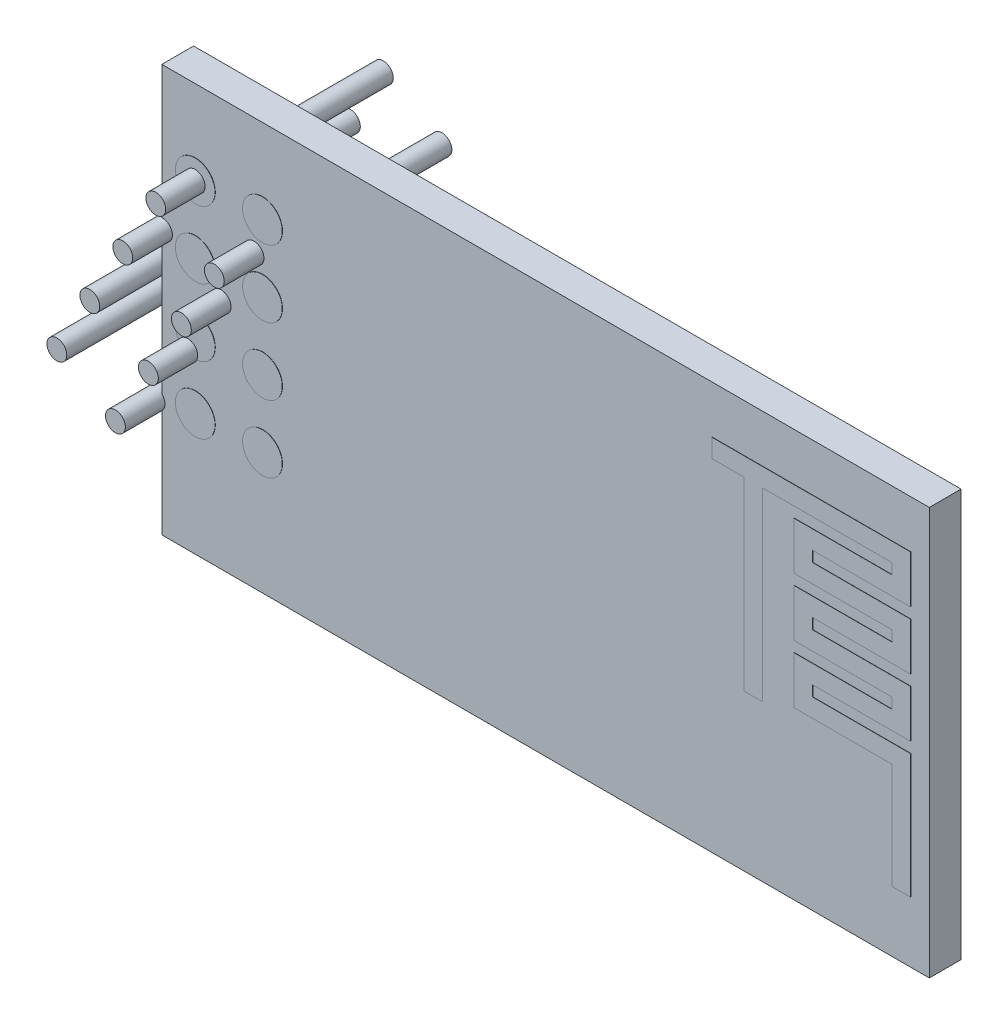
SolidWorks part; units mm, degrees
ref_plane "Front Plane" through (0, 0, 0) normal (0, 0, 1) x (1, 0, 0)
ref_plane "Top Plane" through (0, 0, 0) normal (0, 1, 0) x (1, 0, 0)
ref_plane "Right Plane" through (0, 0, 0) normal (1, 0, 0) x (0, 0, -1)
sketch "Sketch2" plane through (0, 0, 0) normal (0, 0, 1) x (1, 0, 0)
  line L1 (0, 0) -> (29, 0)
  line L2 (0, 0) -> (0, 15.4)
  line L3 (0, 15.4) -> (29, 15.4)
  line L4 (29, 0) -> (29, 15.4)
  dimension "D1" = 29
  dimension "D2" = 15.4
extrude "Boss-Extrude1" add sketch "Sketch2" along normal blind 1.2
sketch "Sketch3" plane through (0, 0, 1.2) normal (0, 0, 1) x (1, 0, 0)
  line L0 (0, 15.4) -> (0, 0) construction
  line L1 (29, 15.4) -> (0, 15.4) construction
  circle A0 centre (1.27, 12.225) radius 0.75
  circle A1 centre (3.81, 12.225) radius 0.75
  circle A2 centre (3.81, 9.685) radius 0.75
  circle A3 centre (3.81, 7.145) radius 0.75
  circle A4 centre (3.81, 4.605) radius 0.75
  circle A5 centre (1.27, 9.685) radius 0.75
  circle A6 centre (1.27, 7.145) radius 0.75
  circle A7 centre (1.27, 4.605) radius 0.75
  dimension "D1" = 1.27
  dimension "D3" = 1.5
  dimension "D2" = 3.175
  dimension "D4" = 2
  dimension "D5" = 4
extrude "Boss-Extrude2" add sketch "Sketch3" along normal blind 0.01
sketch "Sketch4" plane through (0, 0, 1.2) normal (0, 0, 1) x (1, 0, 0)
  circle A0 centre (1.27, 12.225) radius 0.375
  circle A1 centre (3.4833, 10.9789) radius 0.375
  circle A2 centre (2.2372, 8.7656) radius 0.375
  circle A3 centre (0.9912, 6.5522) radius 0.375
  circle A4 centre (-0.2549, 4.3389) radius 0.375
  circle A5 centre (0.0239, 10.0117) radius 0.375
  circle A6 centre (-1.2222, 7.7983) radius 0.375
  circle A7 centre (-2.4683, 5.585) radius 0.375
  dimension "D1" = 0.75
  dimension "D2" = 2
  dimension "D3" = 4
extrude "Boss-Extrude3" add sketch "Sketch4" along normal blind 1.5 and the other way blind 7.1
sketch "Sketch5" plane through (0, 0, 1.2) normal (0, 0, 1) x (1, 0, 0)
  line L0 (20.8, 13.6) -> (28.3, 13.6)
  line L1 (28.3, 13.6) -> (28.3, 11.8)
  line L2 (28.3, 11.8) -> (24.6, 11.8)
  line L3 (24.6, 11.8) -> (24.6, 11.4)
  line L4 (24.6, 11.4) -> (28.3, 11.4)
  line L5 (28.3, 11.4) -> (28.3, 9.6)
  line L6 (28.3, 9.6) -> (24.6, 9.6)
  line L7 (24.6, 9.6) -> (24.6, 9.2)
  line L8 (24.6, 9.2) -> (28.3, 9.2)
  line L9 (28.3, 9.2) -> (28.3, 7.4)
  line L10 (28.3, 7.4) -> (24.6, 7.4)
  line L11 (24.6, 7.4) -> (24.6, 7)
  line L12 (24.6, 7) -> (28.3, 7)
  line L13 (28.3, 7) -> (28.3, 2.3)
  line L14 (28.3, 2.3) -> (27.6, 2.3)
  line L15 (27.6, 2.3) -> (27.6, 6.3)
  line L16 (27.6, 6.3) -> (23.9, 6.3)
  line L17 (23.9, 6.3) -> (23.9, 8.1)
  line L18 (23.9, 8.1) -> (27.6, 8.1)
  line L19 (27.6, 8.1) -> (27.6, 8.5)
  line L20 (27.6, 8.5) -> (23.9, 8.5)
  line L21 (23.9, 8.5) -> (23.9, 10.3)
  line L22 (23.9, 10.3) -> (27.6, 10.3)
  line L23 (27.6, 10.3) -> (27.6, 10.7)
  line L24 (27.6, 10.7) -> (23.9, 10.7)
  line L25 (23.9, 10.7) -> (23.9, 12.5)
  line L26 (23.9, 12.5) -> (27.6, 12.5)
  line L27 (27.6, 12.5) -> (27.6, 12.9)
  line L28 (27.6, 12.9) -> (22.7, 12.9)
  line L29 (22.7, 12.9) -> (22.7, 5.9)
  line L30 (22.7, 5.9) -> (22, 5.9)
  line L31 (22, 5.9) -> (22, 12.9)
  line L32 (22, 12.9) -> (20.8, 12.9)
  line L33 (20.8, 12.9) -> (20.8, 13.6)
  line L34 (29, 15.4) -> (0, 15.4) construction
  line L35 (29, 0) -> (29, 15.4) construction
  point P36 (22.35, 5.9)
  dimension "D1" = 0.7
  dimension "D2" = 0.7
  dimension "D3" = 0.7
  dimension "D4" = 0.7
  dimension "D5" = 0.7
  dimension "D6" = 0.7
  dimension "D7" = 0.7
  dimension "D8" = 0.7
  dimension "D9" = 0.7
  dimension "D10" = 0.7
  dimension "D11" = 1.8
  dimension "D12" = 0.4
  dimension "D13" = 0.4
  dimension "D14" = 0.4
  dimension "D15" = 0.4
  dimension "D16" = 0.4
  dimension "D17" = 0.4
  dimension "D18" = 7
  dimension "D19" = 4
  dimension "D20" = 0.7
  dimension "D21" = 1.2
  dimension "D22" = 7.5
  dimension "D23" = 1.2
extrude "Boss-Extrude4" add sketch "Sketch5" along normal blind 0.01
sketch "Sketch6" plane through (0, 0, 0) normal (0, 0, -1) x (-1, 0, 0)
  line L0 (-29, 15.4) -> (0, 15.4) construction
  line L1 (-5.1, 12.9) -> (-0.1, 12.9)
  line L2 (-5.1, 12.9) -> (-5.1, 2.5)
  line L3 (-5.1, 2.5) -> (-0.1, 2.5)
  line L4 (-0.1, 12.9) -> (-0.1, 2.5)
  line L5 (0, 0) -> (-29, 0) construction
  line L6 (0, 15.4) -> (0, 10.3859) construction
  dimension "D1" = 2.5
  dimension "D2" = 2.5
  dimension "D3" = 0.1
  dimension "D4" = 5
extrude "Boss-Extrude5" add sketch "Sketch6" along normal blind 2.2 separate body
